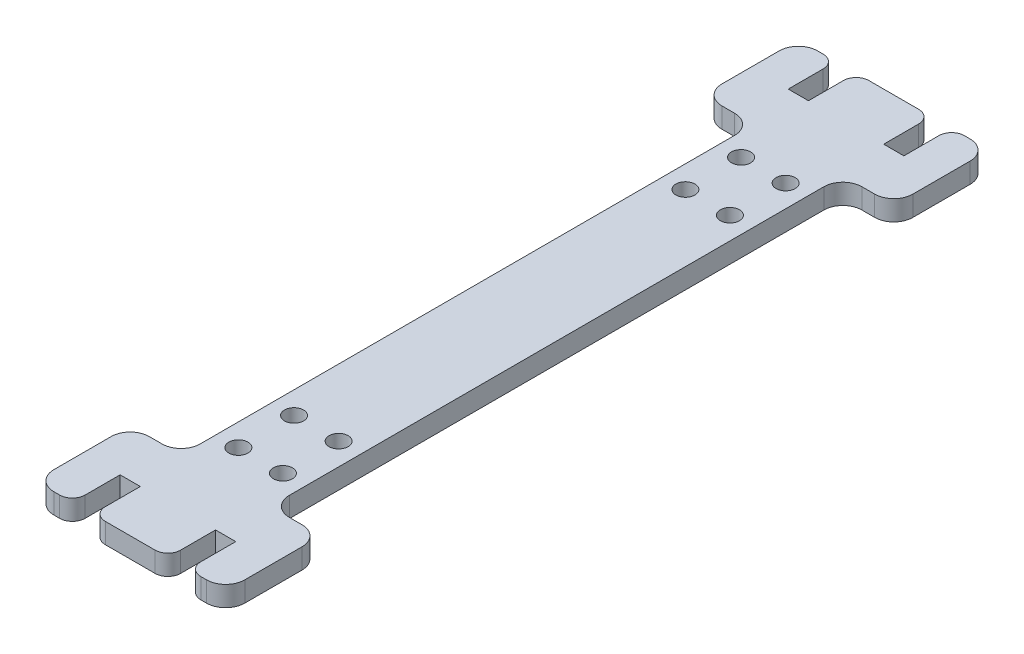
SolidWorks part; units mm, degrees
ref_plane "Front Plane" through (0, 0, 0) normal (0, 0, 1) x (1, 0, 0)
ref_plane "Top Plane" through (0, 0, 0) normal (0, 1, 0) x (1, 0, 0)
ref_plane "Right Plane" through (0, 0, 0) normal (1, 0, 0) x (0, 0, -1)
sketch "Sketch1" plane through (0, 0, 0) normal (0, 1, 0) x (1, 0, 0)
  line L0 (0, 0) -> (0, 60) construction
  line L1 (-15, 60) -> (15, 60)
  line L2 (15, 60) -> (15, 45)
  line L3 (15, 45) -> (7, 45)
  line L4 (7, 45) -> (7, -45)
  line L5 (7, 0) -> (0, 0) construction
  line L6 (-7, 45) -> (-7, -45)
  line L7 (-15, 45) -> (-7, 45)
  line L8 (-15, 60) -> (-15, 45)
  line L9 (15, -45) -> (7, -45)
  line L10 (15, -60) -> (15, -45)
  line L11 (-15, -60) -> (15, -60)
  line L12 (-15, -60) -> (-15, -45)
  line L13 (-15, -45) -> (-7, -45)
  point P17 (-7, 0)
  dimension "D1" = 60
  dimension "D2" = 7
  dimension "D3" = 15
  dimension "D4" = 15
extrude "Boss-Extrude1" add sketch "Sketch1" along normal blind 3.175
sketch "Sketch2" plane through (0, 3.175, 0) normal (0, 1, 0) x (1, 0, 0)
  line L0 (0, 60) -> (0, -60) construction
  line L1 (15, 60) -> (-15, 60) construction
  line L2 (-15, -60) -> (15, -60) construction
  line L8 (15, 45) -> (15, 60) construction
  line L9 (5.9125, 67.5) -> (9.0875, 67.5)
  line L10 (5.9125, 67.5) -> (5.9125, 52.5)
  line L11 (5.9125, 52.5) -> (9.0875, 52.5)
  line L16 (0, 0) -> (7, 0) construction
  line L17 (7, -45) -> (7, 45) construction
  line L18 (9.0875, 67.5) -> (9.0875, 52.5)
  line L19 (5.9125, 67.5) -> (9.0875, 52.5) construction
  line L24 (5.9125, 52.5) -> (9.0875, 67.5) construction
  line L25 (-5.9125, 52.5) -> (-9.0875, 67.5) construction
  line L30 (-5.9125, 67.5) -> (-9.0875, 52.5) construction
  line L31 (-9.0875, 67.5) -> (-9.0875, 52.5)
  line L32 (-5.9125, 52.5) -> (-9.0875, 52.5)
  line L33 (-5.9125, 67.5) -> (-5.9125, 52.5)
  line L34 (-5.9125, 67.5) -> (-9.0875, 67.5)
  line L35 (5.9125, -52.5) -> (9.0875, -67.5) construction
  line L36 (5.9125, -67.5) -> (9.0875, -52.5) construction
  line L37 (9.0875, -67.5) -> (9.0875, -52.5)
  line L38 (5.9125, -52.5) -> (9.0875, -52.5)
  line L39 (5.9125, -67.5) -> (5.9125, -52.5)
  line L40 (5.9125, -67.5) -> (9.0875, -67.5)
  line L41 (-5.9125, -67.5) -> (-9.0875, -52.5) construction
  line L42 (-5.9125, -52.5) -> (-9.0875, -67.5) construction
  line L43 (-5.9125, -67.5) -> (-9.0875, -67.5)
  line L44 (-5.9125, -67.5) -> (-5.9125, -52.5)
  line L45 (-5.9125, -52.5) -> (-9.0875, -52.5)
  line L46 (-9.0875, -67.5) -> (-9.0875, -52.5)
  point P6 (7.5, 60)
  point P17 (-7.5, 60)
  point P27 (7.5, -60)
  point P32 (-7.5, -60)
  dimension "D1" = 7.5
  dimension "D2" = 15
  dimension "D3" = 3.175
extrude "Cut-Extrude1" cut sketch "Sketch2" against normal through all
sketch "Sketch5" plane through (0, 0, 0) normal (0, -1, 0) x (1, 0, 0)
  circle A0 centre (3.5, 30.75) radius 1.5 construction
  circle A1 centre (3.5, -39.5) radius 1.5
  circle A2 centre (3.5, -39.5) radius 1.5
  circle A3 centre (-3.5, -39.5) radius 1.5
  circle A4 centre (-3.5, -39.5) radius 1.5
  circle A5 centre (-3.5, -30.75) radius 1.5
  circle A6 centre (-3.5, -30.75) radius 1.5
  circle A7 centre (-3.5, 30.75) radius 1.5 construction
  circle A8 centre (3.5, 39.5) radius 1.5 construction
  circle A9 centre (-3.5, 39.5) radius 1.5 construction
  circle A10 centre (3.5, 30.75) radius 1.5
  circle A11 centre (-3.5, 30.75) radius 1.5
  circle A12 centre (3.5, 39.5) radius 1.5
  circle A13 centre (-3.5, 39.5) radius 1.5
  circle A17 centre (3.5, -30.75) radius 1.5
  dimension "D4" = 3
  dimension "D1" = 0
  dimension "D2" = 0
  dimension "D3" = 0
extrude "Cut-Extrude2" cut sketch "Sketch5" against normal blind 10
fillet "Fillet1" radius 2 8 edges at (-5.9125, 1.5875, 60) (-9.0875, 1.5875, 60) (5.9125, 1.5875, 60) (9.0875, 1.5875, 60) (9.0875, 1.5875, -60) (5.9125, 1.5875, -60) (-5.9125, 1.5875, -60) (-9.0875, 1.5875, -60)
fillet "Fillet2" radius 3 12 edges at (-15, 1.5875, 60) (-15, 1.5875, 45) (-7, 1.5875, 45) (15, 1.5875, 60) (15, 1.5875, 45) (7, 1.5875, 45) (15, 1.5875, -60) (15, 1.5875, -45) (7, 1.5875, -45) (-7, 1.5875, -45) (-15, 1.5875, -45) (-15, 1.5875, -60)
